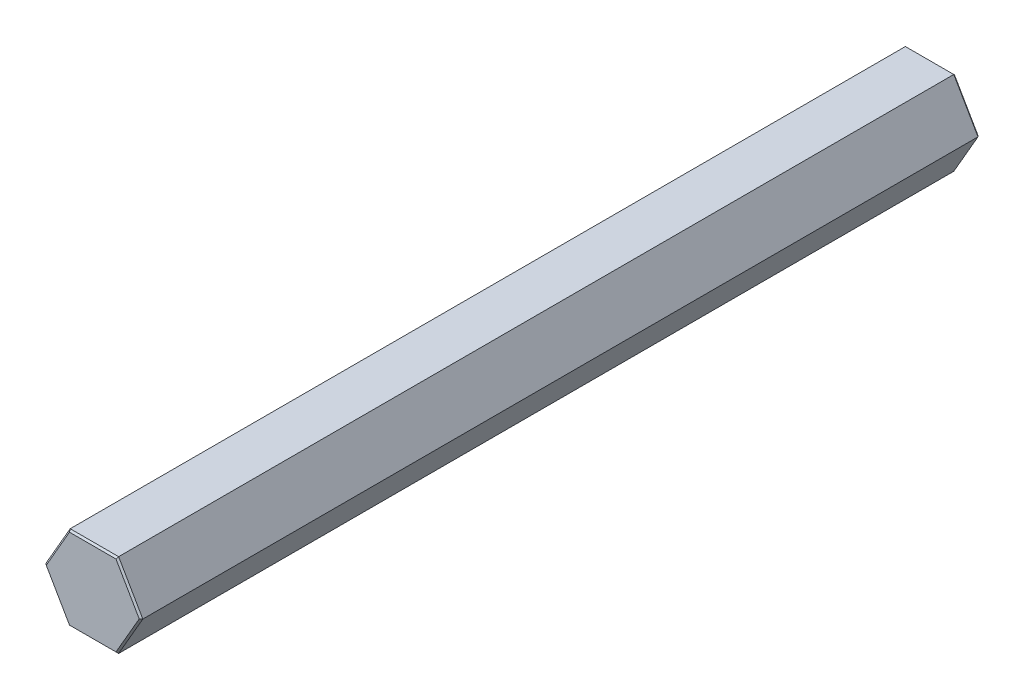
SolidWorks part; units mm, degrees
ref_plane "Front Plane" through (0, 0, 0) normal (0, 0, 1) x (1, 0, 0)
ref_plane "Top Plane" through (0, 0, 0) normal (0, 1, 0) x (1, 0, 0)
ref_plane "Right Plane" through (0, 0, 0) normal (1, 0, 0) x (0, 0, -1)
ref_plane "Plane1" through (0, 0, 127) normal (0, 0, 1) x (1, 0, 0)
sketch "Sketch1" plane through (0, 0, 127) normal (0, 0, 1) x (1, 0, 0)
  line L0 (3.6662, -6.35) -> (7.3323, 0)
  line L1 (7.3323, 0) -> (3.6662, 6.35)
  line L2 (3.6662, 6.35) -> (-3.6662, 6.35)
  line L3 (-3.6662, 6.35) -> (-7.3323, 0)
  line L4 (-7.3323, 0) -> (-3.6662, -6.35)
  line L5 (-3.6662, -6.35) -> (3.6662, -6.35)
extrude "Boss-Extrude1" add sketch "Sketch1" against normal blind 127
chamfer "Chamfer1" distance 0.254 angle 45 12 edges at (0, 6.35, 0) (-5.4993, 3.175, 0) (5.4993, 3.175, 0) (-5.4993, -3.175, 0) (5.4993, -3.175, 0) (0, -6.35, 0) (-5.4993, 3.175, 127) (-5.4993, -3.175, 127) (0, 6.35, 127) (0, -6.35, 127) (5.4993, 3.175, 127) (5.4993, -3.175, 127)
